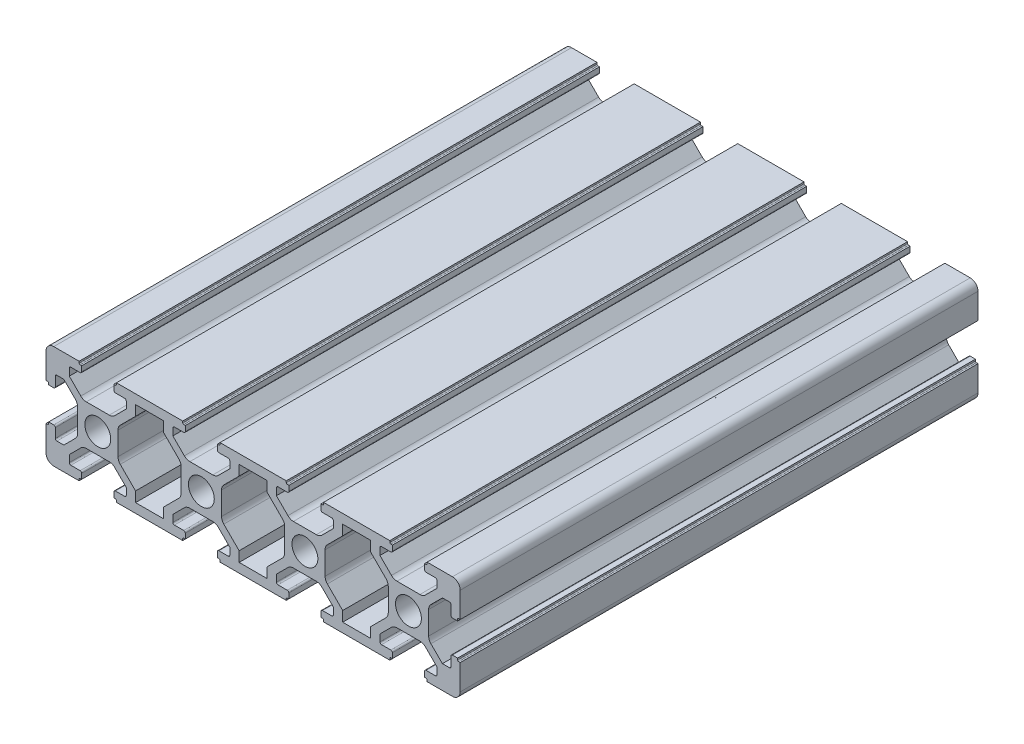
SolidWorks part; units mm, degrees
ref_plane "前视基准面" through (0, 0, 0) normal (0, 0, 1) x (1, 0, 0)
ref_plane "上视基准面" through (0, 0, 0) normal (0, 1, 0) x (1, 0, 0)
ref_plane "右视基准面" through (0, 0, 0) normal (1, 0, 0) x (0, 0, -1)
sketch "草图1" plane through (0, 0, 0) normal (0, 0, 1) x (1, 0, 0)
  line L0 (-31.421, -14.7038) -> (-34.3817, -11.7431)
  line L1 (-34.821, -10.6824) -> (-34.821, -6.2451)
  line L2 (-34.3817, -5.1844) -> (-31.421, -2.2238)
  line L3 (-30.221, 1.5362) -> (-35.121, 1.5362)
  line L4 (-35.121, 1.5362) -> (-35.121, 1.2362)
  line L5 (-35.321, 1.0362) -> (-35.621, 1.0362)
  line L6 (-35.621, 1.0362) -> (-35.621, 0.0362)
  line L7 (-35.321, -0.2638) -> (-33.521, -0.2638)
  line L8 (-33.221, -0.5638) -> (-33.221, -1.9038)
  line L9 (-33.221, -1.9038) -> (-35.4417, -4.1244)
  line L10 (-36.5023, -4.5638) -> (-40.9397, -4.5638)
  line L11 (-42.0003, -4.1244) -> (-44.221, -1.9038)
  line L12 (-44.221, -1.9038) -> (-44.221, -0.5638)
  line L13 (-43.921, -0.2638) -> (-42.121, -0.2638)
  line L14 (-41.821, 0.0362) -> (-41.821, 1.0362)
  line L15 (-41.821, 1.0362) -> (-42.121, 1.0362)
  line L16 (-42.321, 1.2362) -> (-42.321, 1.5362)
  line L17 (-42.321, 1.5362) -> (-47.221, 1.5362)
  line L18 (-48.721, 0.0362) -> (-48.721, -4.8638)
  line L19 (-48.721, -4.8638) -> (-48.421, -4.8638)
  line L20 (-48.221, -5.0638) -> (-48.221, -5.3638)
  line L21 (-48.221, -5.3638) -> (-47.221, -5.3638)
  line L22 (-46.921, -5.0638) -> (-46.921, -3.2638)
  line L23 (-46.621, -2.9638) -> (-45.281, -2.9638)
  line L24 (-45.281, -2.9638) -> (-43.0603, -5.1844)
  line L25 (-42.621, -6.2451) -> (-42.621, -10.6824)
  line L26 (-43.0603, -11.7431) -> (-45.281, -13.9638)
  line L27 (-45.281, -13.9638) -> (-46.621, -13.9638)
  line L28 (-46.921, -13.6638) -> (-46.921, -11.8638)
  line L29 (-47.221, -11.5638) -> (-48.221, -11.5638)
  line L30 (-48.221, -11.5638) -> (-48.221, -11.8638)
  line L31 (-48.421, -12.0638) -> (-48.721, -12.0638)
  line L32 (-48.721, -12.0638) -> (-48.721, -16.9638)
  line L33 (-47.221, -18.4638) -> (-42.321, -18.4638)
  line L34 (-42.321, -18.4638) -> (-42.321, -18.1638)
  line L35 (-42.121, -17.9638) -> (-41.821, -17.9638)
  line L36 (-41.821, -17.9638) -> (-41.821, -16.9638)
  line L37 (-42.121, -16.6638) -> (-43.921, -16.6638)
  line L38 (-44.221, -16.3638) -> (-44.221, -15.0238)
  line L39 (-44.221, -15.0238) -> (-42.0003, -12.8031)
  line L40 (-40.9397, -12.3638) -> (-36.5023, -12.3638)
  line L41 (-35.4417, -12.8031) -> (-33.221, -15.0238)
  line L42 (-33.221, -15.0238) -> (-33.221, -16.3638)
  line L43 (-33.521, -16.6638) -> (-35.321, -16.6638)
  line L44 (-35.621, -16.9638) -> (-35.621, -17.9638)
  line L45 (-35.621, -17.9638) -> (-35.321, -17.9638)
  line L46 (-35.121, -18.1638) -> (-35.121, -18.4638)
  line L47 (-35.121, -18.4638) -> (-30.221, -18.4638)
  line L48 (-30.221, -18.4638) -> (-22.321, -18.4638)
  line L49 (-22.321, -18.4638) -> (-22.321, -18.1638)
  line L50 (-22.121, -17.9638) -> (-21.821, -17.9638)
  line L51 (-21.821, -17.9638) -> (-21.821, -16.9638)
  line L52 (-22.121, -16.6638) -> (-23.921, -16.6638)
  line L53 (-24.221, -16.3638) -> (-24.221, -15.0238)
  line L54 (-24.221, -15.0238) -> (-22.0003, -12.8031)
  line L55 (-20.9397, -12.3638) -> (-16.5023, -12.3638)
  line L56 (-15.4417, -12.8031) -> (-13.221, -15.0238)
  line L57 (-13.221, -15.0238) -> (-13.221, -16.3638)
  line L58 (-13.521, -16.6638) -> (-15.321, -16.6638)
  line L59 (-15.621, -16.9638) -> (-15.621, -17.9638)
  line L60 (-15.621, -17.9638) -> (-15.321, -17.9638)
  line L61 (-15.121, -18.1638) -> (-15.121, -18.4638)
  line L62 (-15.121, -18.4638) -> (-10.221, -18.4638)
  line L64 (-14.821, -10.6824) -> (-14.821, -6.2451)
  line L66 (-10.221, 1.5362) -> (-15.121, 1.5362)
  line L67 (-15.121, 1.5362) -> (-15.121, 1.2362)
  line L68 (-15.321, 1.0362) -> (-15.621, 1.0362)
  line L69 (-15.621, 1.0362) -> (-15.621, 0.0362)
  line L70 (-15.321, -0.2638) -> (-13.521, -0.2638)
  line L71 (-13.221, -0.5638) -> (-13.221, -1.9038)
  line L72 (-13.221, -1.9038) -> (-15.4417, -4.1244)
  line L73 (-16.5023, -4.5638) -> (-20.9397, -4.5638)
  line L74 (-22.0003, -4.1244) -> (-24.221, -1.9038)
  line L75 (-24.221, -1.9038) -> (-24.221, -0.5638)
  line L76 (-23.921, -0.2638) -> (-22.121, -0.2638)
  line L77 (-21.821, 0.0362) -> (-21.821, 1.0362)
  line L78 (-21.821, 1.0362) -> (-22.121, 1.0362)
  line L79 (-22.321, 1.2362) -> (-22.321, 1.5362)
  line L80 (-22.321, 1.5362) -> (-27.221, 1.5362)
  line L81 (-26.021, -2.2238) -> (-23.0603, -5.1844)
  line L82 (-22.621, -6.2451) -> (-22.621, -10.6824)
  line L83 (-23.0603, -11.7431) -> (-26.021, -14.7038)
  line L84 (-30.221, 1.5362) -> (-27.221, 1.5362)
  line L85 (-10.221, -18.4638) -> (-2.321, -18.4638)
  line L86 (9.779, -18.4638) -> (17.679, -18.4638)
  line L87 (-31.421, -0.2638) -> (-26.021, -0.2638)
  line L88 (-26.021, -0.2638) -> (-26.021, -2.2238)
  line L89 (-31.421, -0.2638) -> (-31.421, -2.2238)
  line L90 (-31.421, -16.6638) -> (-26.021, -16.6638)
  line L91 (-26.021, -16.6638) -> (-26.021, -14.7038)
  line L92 (-31.421, -16.6638) -> (-31.421, -14.7038)
  line L93 (-2.321, 1.5362) -> (-10.221, 1.5362)
  line L186 (17.679, -18.4638) -> (17.679, -18.1638)
  line L187 (17.879, -17.9638) -> (18.179, -17.9638)
  line L188 (18.179, -17.9638) -> (18.179, -16.9638)
  line L189 (17.879, -16.6638) -> (16.079, -16.6638)
  line L190 (15.779, -16.3638) -> (15.779, -15.0238)
  line L191 (15.779, -15.0238) -> (17.9997, -12.8031)
  line L192 (19.0603, -12.3638) -> (23.4977, -12.3638)
  line L193 (24.5583, -12.8031) -> (26.779, -15.0238)
  line L194 (26.779, -15.0238) -> (26.779, -16.3638)
  line L195 (26.479, -16.6638) -> (24.679, -16.6638)
  line L196 (24.379, -16.9638) -> (24.379, -17.9638)
  line L197 (24.379, -17.9638) -> (24.679, -17.9638)
  line L198 (24.879, -18.1638) -> (24.879, -18.4638)
  line L199 (24.879, -18.4638) -> (29.779, -18.4638)
  line L200 (31.279, -16.9638) -> (31.279, -12.0638)
  line L201 (31.279, -12.0638) -> (30.979, -12.0638)
  line L202 (30.779, -11.8638) -> (30.779, -11.5638)
  line L203 (30.779, -11.5638) -> (29.779, -11.5638)
  line L204 (29.479, -11.8638) -> (29.479, -13.6638)
  line L205 (29.179, -13.9638) -> (27.839, -13.9638)
  line L206 (27.839, -13.9638) -> (25.6183, -11.7431)
  line L207 (25.179, -10.6824) -> (25.179, -6.2451)
  line L208 (25.6183, -5.1844) -> (27.839, -2.9638)
  line L209 (27.839, -2.9638) -> (29.179, -2.9638)
  line L210 (29.479, -3.2638) -> (29.479, -5.0638)
  line L211 (29.779, -5.3638) -> (30.779, -5.3638)
  line L212 (30.779, -5.3638) -> (30.779, -5.0638)
  line L213 (30.979, -4.8638) -> (31.279, -4.8638)
  line L214 (31.279, -4.8638) -> (31.279, 0.0362)
  line L215 (29.779, 1.5362) -> (24.879, 1.5362)
  line L216 (24.879, 1.5362) -> (24.879, 1.2362)
  line L217 (24.679, 1.0362) -> (24.379, 1.0362)
  line L218 (24.379, 1.0362) -> (24.379, 0.0362)
  line L219 (24.679, -0.2638) -> (26.479, -0.2638)
  line L220 (26.779, -0.5638) -> (26.779, -1.9038)
  line L221 (26.779, -1.9038) -> (24.5583, -4.1244)
  line L222 (23.4977, -4.5638) -> (19.0603, -4.5638)
  line L223 (17.9997, -4.1244) -> (15.779, -1.9038)
  line L224 (15.779, -1.9038) -> (15.779, -0.5638)
  line L225 (16.079, -0.2638) -> (17.879, -0.2638)
  line L226 (18.179, 0.0362) -> (18.179, 1.0362)
  line L227 (18.179, 1.0362) -> (17.879, 1.0362)
  line L228 (17.679, 1.2362) -> (17.679, 1.5362)
  line L229 (17.679, 1.5362) -> (12.779, 1.5362)
  line L230 (5.6183, -5.1844) -> (8.579, -2.2238)
  line L231 (8.579, -2.2238) -> (8.579, -0.2638)
  line L232 (8.579, -0.2638) -> (13.979, -0.2638)
  line L233 (13.979, -0.2638) -> (13.979, -2.2238)
  line L234 (13.979, -2.2238) -> (16.9397, -5.1844)
  line L235 (17.379, -6.2451) -> (17.379, -10.6824)
  line L236 (16.9397, -11.7431) -> (13.979, -14.7038)
  line L237 (13.979, -14.7038) -> (13.979, -16.6638)
  line L238 (13.979, -16.6638) -> (8.579, -16.6638)
  line L239 (8.579, -16.6638) -> (8.579, -14.7038)
  line L240 (8.579, -14.7038) -> (5.6183, -11.7431)
  line L241 (5.179, -10.6824) -> (5.179, -6.2451)
  line L243 (-2.621, -6.2451) -> (-2.621, -10.6824)
  line L246 (-2.321, -18.4638) -> (-2.321, -18.1638)
  line L247 (-2.121, -17.9638) -> (-1.821, -17.9638)
  line L248 (-1.821, -17.9638) -> (-1.821, -16.9638)
  line L249 (-2.121, -16.6638) -> (-3.921, -16.6638)
  line L250 (-4.221, -16.3638) -> (-4.221, -15.0238)
  line L251 (-4.221, -15.0238) -> (-2.0003, -12.8031)
  line L252 (-0.9397, -12.3638) -> (3.4977, -12.3638)
  line L253 (4.5583, -12.8031) -> (6.779, -15.0238)
  line L254 (6.779, -15.0238) -> (6.779, -16.3638)
  line L255 (6.479, -16.6638) -> (4.679, -16.6638)
  line L256 (4.379, -16.9638) -> (4.379, -17.9638)
  line L257 (4.379, -17.9638) -> (4.679, -17.9638)
  line L258 (4.879, -18.1638) -> (4.879, -18.4638)
  line L259 (4.879, -18.4638) -> (9.779, -18.4638)
  line L306 (12.779, 1.5362) -> (9.779, 1.5362)
  line L307 (9.779, 1.5362) -> (4.879, 1.5362)
  line L308 (4.879, 1.5362) -> (4.879, 1.2362)
  line L309 (4.679, 1.0362) -> (4.379, 1.0362)
  line L310 (4.379, 1.0362) -> (4.379, 0.0362)
  line L311 (4.679, -0.2638) -> (6.479, -0.2638)
  line L312 (6.779, -0.5638) -> (6.779, -1.9038)
  line L313 (6.779, -1.9038) -> (4.5583, -4.1244)
  line L314 (3.4977, -4.5638) -> (-0.9397, -4.5638)
  line L315 (-2.0003, -4.1244) -> (-4.221, -1.9038)
  line L316 (-4.221, -1.9038) -> (-4.221, -0.5638)
  line L317 (-3.921, -0.2638) -> (-2.121, -0.2638)
  line L318 (-1.821, 0.0362) -> (-1.821, 1.0362)
  line L319 (-1.821, 1.0362) -> (-2.121, 1.0362)
  line L320 (-2.321, 1.2362) -> (-2.321, 1.5362)
  line L323 (-11.421, -2.2238) -> (-11.421, -0.2638)
  line L324 (-11.421, -0.2638) -> (-6.021, -0.2638)
  line L325 (-6.021, -0.2638) -> (-6.021, -2.2238)
  line L326 (-6.021, -2.2238) -> (-3.0603, -5.1844)
  line L329 (-6.021, -14.7038) -> (-6.021, -16.6638)
  line L330 (-6.021, -16.6638) -> (-11.421, -16.6638)
  line L331 (-11.421, -16.6638) -> (-11.421, -14.7038)
  line L332 (-11.421, -14.7038) -> (-14.3817, -11.7431)
  line L360 (-14.3817, -5.1844) -> (-11.421, -2.2238)
  line L366 (-3.0603, -11.7431) -> (-6.021, -14.7038)
  arc A1 (-34.821, -10.6824) -> (-34.3817, -11.7431) centre (-33.321, -10.6824) ccw
  arc A2 (-34.3817, -5.1844) -> (-34.821, -6.2451) centre (-33.321, -6.2451) ccw
  arc A3 (-35.321, 1.0362) -> (-35.121, 1.2362) centre (-35.321, 1.2362) ccw
  arc A4 (-35.621, 0.0362) -> (-35.321, -0.2638) centre (-35.321, 0.0362) ccw
  arc A5 (-33.221, -0.5638) -> (-33.521, -0.2638) centre (-33.521, -0.5638) ccw
  arc A6 (-36.5023, -4.5638) -> (-35.4417, -4.1244) centre (-36.5023, -3.0638) ccw
  arc A7 (-42.0003, -4.1244) -> (-40.9397, -4.5638) centre (-40.9397, -3.0638) ccw
  arc A8 (-43.921, -0.2638) -> (-44.221, -0.5638) centre (-43.921, -0.5638) ccw
  arc A9 (-42.121, -0.2638) -> (-41.821, 0.0362) centre (-42.121, 0.0362) ccw
  arc A10 (-42.321, 1.2362) -> (-42.121, 1.0362) centre (-42.121, 1.2362) ccw
  arc A11 (-47.221, 1.5362) -> (-48.721, 0.0362) centre (-47.221, 0.0362) ccw
  arc A12 (-48.221, -5.0638) -> (-48.421, -4.8638) centre (-48.421, -5.0638) ccw
  arc A13 (-47.221, -5.3638) -> (-46.921, -5.0638) centre (-47.221, -5.0638) ccw
  arc A14 (-46.621, -2.9638) -> (-46.921, -3.2638) centre (-46.621, -3.2638) ccw
  arc A15 (-42.621, -6.2451) -> (-43.0603, -5.1844) centre (-44.121, -6.2451) ccw
  arc A16 (-43.0603, -11.7431) -> (-42.621, -10.6824) centre (-44.121, -10.6824) ccw
  arc A17 (-46.921, -13.6638) -> (-46.621, -13.9638) centre (-46.621, -13.6638) ccw
  arc A18 (-46.921, -11.8638) -> (-47.221, -11.5638) centre (-47.221, -11.8638) ccw
  arc A19 (-48.421, -12.0638) -> (-48.221, -11.8638) centre (-48.421, -11.8638) ccw
  arc A20 (-48.721, -16.9638) -> (-47.221, -18.4638) centre (-47.221, -16.9638) ccw
  arc A21 (-42.121, -17.9638) -> (-42.321, -18.1638) centre (-42.121, -18.1638) ccw
  arc A22 (-41.821, -16.9638) -> (-42.121, -16.6638) centre (-42.121, -16.9638) ccw
  arc A23 (-44.221, -16.3638) -> (-43.921, -16.6638) centre (-43.921, -16.3638) ccw
  arc A24 (-40.9397, -12.3638) -> (-42.0003, -12.8031) centre (-40.9397, -13.8638) ccw
  arc A25 (-35.4417, -12.8031) -> (-36.5023, -12.3638) centre (-36.5023, -13.8638) ccw
  arc A26 (-33.521, -16.6638) -> (-33.221, -16.3638) centre (-33.521, -16.3638) ccw
  arc A27 (-35.321, -16.6638) -> (-35.621, -16.9638) centre (-35.321, -16.9638) ccw
  arc A28 (-35.121, -18.1638) -> (-35.321, -17.9638) centre (-35.321, -18.1638) ccw
  arc A29 (-22.121, -17.9638) -> (-22.321, -18.1638) centre (-22.121, -18.1638) ccw
  arc A30 (-21.821, -16.9638) -> (-22.121, -16.6638) centre (-22.121, -16.9638) ccw
  arc A31 (-24.221, -16.3638) -> (-23.921, -16.6638) centre (-23.921, -16.3638) ccw
  arc A32 (-20.9397, -12.3638) -> (-22.0003, -12.8031) centre (-20.9397, -13.8638) ccw
  arc A33 (-15.4417, -12.8031) -> (-16.5023, -12.3638) centre (-16.5023, -13.8638) ccw
  arc A34 (-13.521, -16.6638) -> (-13.221, -16.3638) centre (-13.521, -16.3638) ccw
  arc A35 (-15.321, -16.6638) -> (-15.621, -16.9638) centre (-15.321, -16.9638) ccw
  arc A36 (-15.121, -18.1638) -> (-15.321, -17.9638) centre (-15.321, -18.1638) ccw
  arc A37 (-14.821, -10.6824) -> (-14.3817, -11.7431) centre (-13.321, -10.6824) ccw
  arc A38 (-14.3817, -5.1844) -> (-14.821, -6.2451) centre (-13.321, -6.2451) ccw
  arc A39 (-15.321, 1.0362) -> (-15.121, 1.2362) centre (-15.321, 1.2362) ccw
  arc A40 (-15.621, 0.0362) -> (-15.321, -0.2638) centre (-15.321, 0.0362) ccw
  arc A41 (-13.221, -0.5638) -> (-13.521, -0.2638) centre (-13.521, -0.5638) ccw
  arc A42 (-16.5023, -4.5638) -> (-15.4417, -4.1244) centre (-16.5023, -3.0638) ccw
  arc A43 (-22.0003, -4.1244) -> (-20.9397, -4.5638) centre (-20.9397, -3.0638) ccw
  arc A44 (-23.921, -0.2638) -> (-24.221, -0.5638) centre (-23.921, -0.5638) ccw
  arc A45 (-22.121, -0.2638) -> (-21.821, 0.0362) centre (-22.121, 0.0362) ccw
  arc A46 (-22.321, 1.2362) -> (-22.121, 1.0362) centre (-22.121, 1.2362) ccw
  arc A47 (-22.621, -6.2451) -> (-23.0603, -5.1844) centre (-24.121, -6.2451) ccw
  arc A48 (-23.0603, -11.7431) -> (-22.621, -10.6824) centre (-24.121, -10.6824) ccw
  arc A100 (17.879, -17.9638) -> (17.679, -18.1638) centre (17.879, -18.1638) ccw
  arc A101 (18.179, -16.9638) -> (17.879, -16.6638) centre (17.879, -16.9638) ccw
  arc A102 (15.779, -16.3638) -> (16.079, -16.6638) centre (16.079, -16.3638) ccw
  arc A103 (19.0603, -12.3638) -> (17.9997, -12.8031) centre (19.0603, -13.8638) ccw
  arc A104 (24.5583, -12.8031) -> (23.4977, -12.3638) centre (23.4977, -13.8638) ccw
  arc A105 (26.479, -16.6638) -> (26.779, -16.3638) centre (26.479, -16.3638) ccw
  arc A106 (24.679, -16.6638) -> (24.379, -16.9638) centre (24.679, -16.9638) ccw
  arc A107 (24.879, -18.1638) -> (24.679, -17.9638) centre (24.679, -18.1638) ccw
  arc A108 (29.779, -18.4638) -> (31.279, -16.9638) centre (29.779, -16.9638) ccw
  arc A109 (30.779, -11.8638) -> (30.979, -12.0638) centre (30.979, -11.8638) ccw
  arc A110 (29.779, -11.5638) -> (29.479, -11.8638) centre (29.779, -11.8638) ccw
  arc A111 (29.179, -13.9638) -> (29.479, -13.6638) centre (29.179, -13.6638) ccw
  arc A112 (25.179, -10.6824) -> (25.6183, -11.7431) centre (26.679, -10.6824) ccw
  arc A113 (25.6183, -5.1844) -> (25.179, -6.2451) centre (26.679, -6.2451) ccw
  arc A114 (29.479, -3.2638) -> (29.179, -2.9638) centre (29.179, -3.2638) ccw
  arc A115 (29.479, -5.0638) -> (29.779, -5.3638) centre (29.779, -5.0638) ccw
  arc A116 (30.979, -4.8638) -> (30.779, -5.0638) centre (30.979, -5.0638) ccw
  arc A117 (31.279, 0.0362) -> (29.779, 1.5362) centre (29.779, 0.0362) ccw
  arc A118 (24.679, 1.0362) -> (24.879, 1.2362) centre (24.679, 1.2362) ccw
  arc A119 (24.379, 0.0362) -> (24.679, -0.2638) centre (24.679, 0.0362) ccw
  arc A120 (26.779, -0.5638) -> (26.479, -0.2638) centre (26.479, -0.5638) ccw
  arc A121 (23.4977, -4.5638) -> (24.5583, -4.1244) centre (23.4977, -3.0638) ccw
  arc A122 (17.9997, -4.1244) -> (19.0603, -4.5638) centre (19.0603, -3.0638) ccw
  arc A123 (16.079, -0.2638) -> (15.779, -0.5638) centre (16.079, -0.5638) ccw
  arc A124 (17.879, -0.2638) -> (18.179, 0.0362) centre (17.879, 0.0362) ccw
  arc A125 (17.679, 1.2362) -> (17.879, 1.0362) centre (17.879, 1.2362) ccw
  arc A128 (17.379, -6.2451) -> (16.9397, -5.1844) centre (15.879, -6.2451) ccw
  arc A129 (16.9397, -11.7431) -> (17.379, -10.6824) centre (15.879, -10.6824) ccw
  arc A130 (5.179, -10.6824) -> (5.6183, -11.7431) centre (6.679, -10.6824) ccw
  arc A131 (5.6183, -5.1844) -> (5.179, -6.2451) centre (6.679, -6.2451) ccw
  arc A133 (-2.621, -6.2451) -> (-3.0603, -5.1844) centre (-4.121, -6.2451) ccw
  arc A134 (-3.0603, -11.7431) -> (-2.621, -10.6824) centre (-4.121, -10.6824) ccw
  arc A135 (-2.121, -17.9638) -> (-2.321, -18.1638) centre (-2.121, -18.1638) ccw
  arc A136 (-1.821, -16.9638) -> (-2.121, -16.6638) centre (-2.121, -16.9638) ccw
  arc A137 (-4.221, -16.3638) -> (-3.921, -16.6638) centre (-3.921, -16.3638) ccw
  arc A138 (-0.9397, -12.3638) -> (-2.0003, -12.8031) centre (-0.9397, -13.8638) ccw
  arc A139 (4.5583, -12.8031) -> (3.4977, -12.3638) centre (3.4977, -13.8638) ccw
  arc A140 (6.479, -16.6638) -> (6.779, -16.3638) centre (6.479, -16.3638) ccw
  arc A141 (4.679, -16.6638) -> (4.379, -16.9638) centre (4.679, -16.9638) ccw
  arc A142 (4.879, -18.1638) -> (4.679, -17.9638) centre (4.679, -18.1638) ccw
  arc A169 (4.679, 1.0362) -> (4.879, 1.2362) centre (4.679, 1.2362) ccw
  arc A170 (4.379, 0.0362) -> (4.679, -0.2638) centre (4.679, 0.0362) ccw
  arc A171 (6.779, -0.5638) -> (6.479, -0.2638) centre (6.479, -0.5638) ccw
  arc A172 (3.4977, -4.5638) -> (4.5583, -4.1244) centre (3.4977, -3.0638) ccw
  arc A173 (-2.0003, -4.1244) -> (-0.9397, -4.5638) centre (-0.9397, -3.0638) ccw
  arc A174 (-3.921, -0.2638) -> (-4.221, -0.5638) centre (-3.921, -0.5638) ccw
  arc A175 (-2.121, -0.2638) -> (-1.821, 0.0362) centre (-2.121, 0.0362) ccw
  arc A176 (-2.321, 1.2362) -> (-2.121, 1.0362) centre (-2.121, 1.2362) ccw
  circle A181 centre (21.279, -8.4638) radius 2.5
  circle A186 centre (-38.721, -8.4638) radius 2.5
  circle A187 centre (1.279, -8.4638) radius 2.5
  circle A192 centre (-18.721, -8.4638) radius 2.5
extrude "凸台-拉伸1" add sketch "草图1" along normal blind 100
